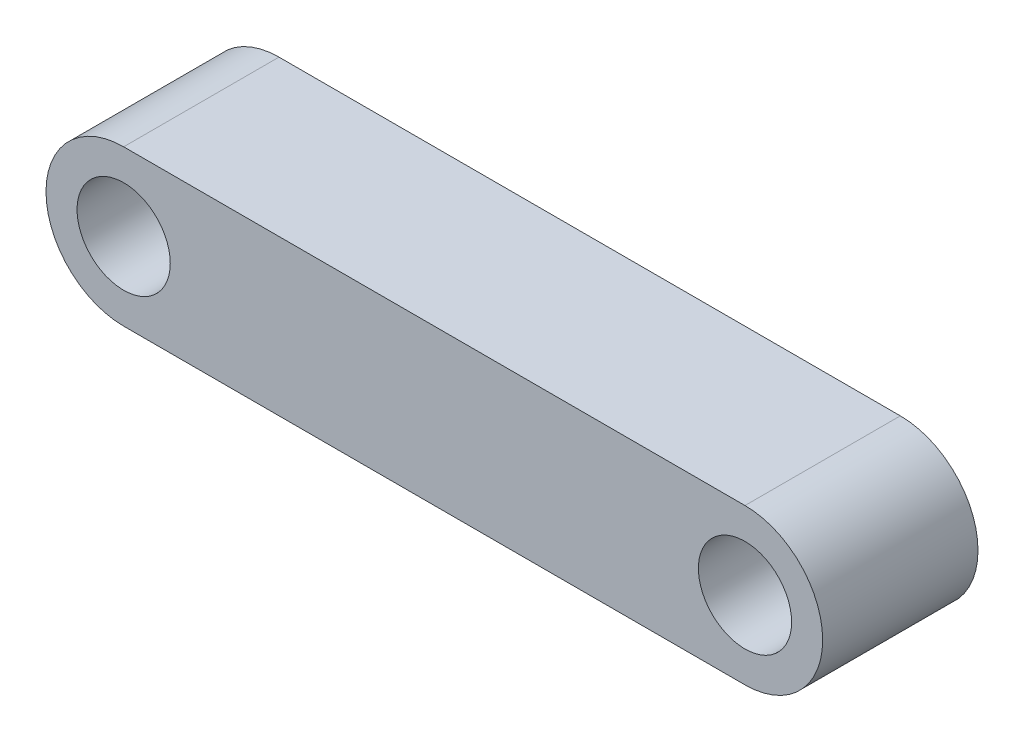
SolidWorks part; units mm, degrees
ref_plane "Front Plane" through (0, 0, 0) normal (0, 0, 1) x (1, 0, 0)
ref_plane "Top Plane" through (0, 0, 0) normal (0, 1, 0) x (1, 0, 0)
ref_plane "Right Plane" through (0, 0, 0) normal (1, 0, 0) x (0, 0, -1)
sketch "Sketch1" plane through (0, 0, 0) normal (0, 0, 1) x (1, 0, 0)
  line L1 (40, -10) -> (-40, -10)
  line L3 (40, 10) -> (-40, 10)
  line L5 (40, -10) -> (-40, 10) construction
  line L6 (40, 10) -> (-40, -10) construction
  arc A0 (-40, 10) -> (-40, -10) centre (-40, 0) ccw
  arc A1 (40, 10) -> (40, -10) centre (40, 0) cw
  point P0 (0, 0)
  point P7 (-50, 0)
  point P9 (50, 0)
  dimension "D3" = 100
  dimension "D1" = 80
  dimension "D2" = 20
extrude "Boss-Extrude1" add sketch "Sketch1" along normal blind 20
sketch "Sketch2" plane through (0, 0, 20) normal (0, 0, 1) x (1, 0, 0)
  circle A0 centre (-40, 0) radius 6
  circle A1 centre (40, 0) radius 6
  dimension "D1" = 12
extrude "Cut-Extrude1" cut sketch "Sketch2" against normal through all
